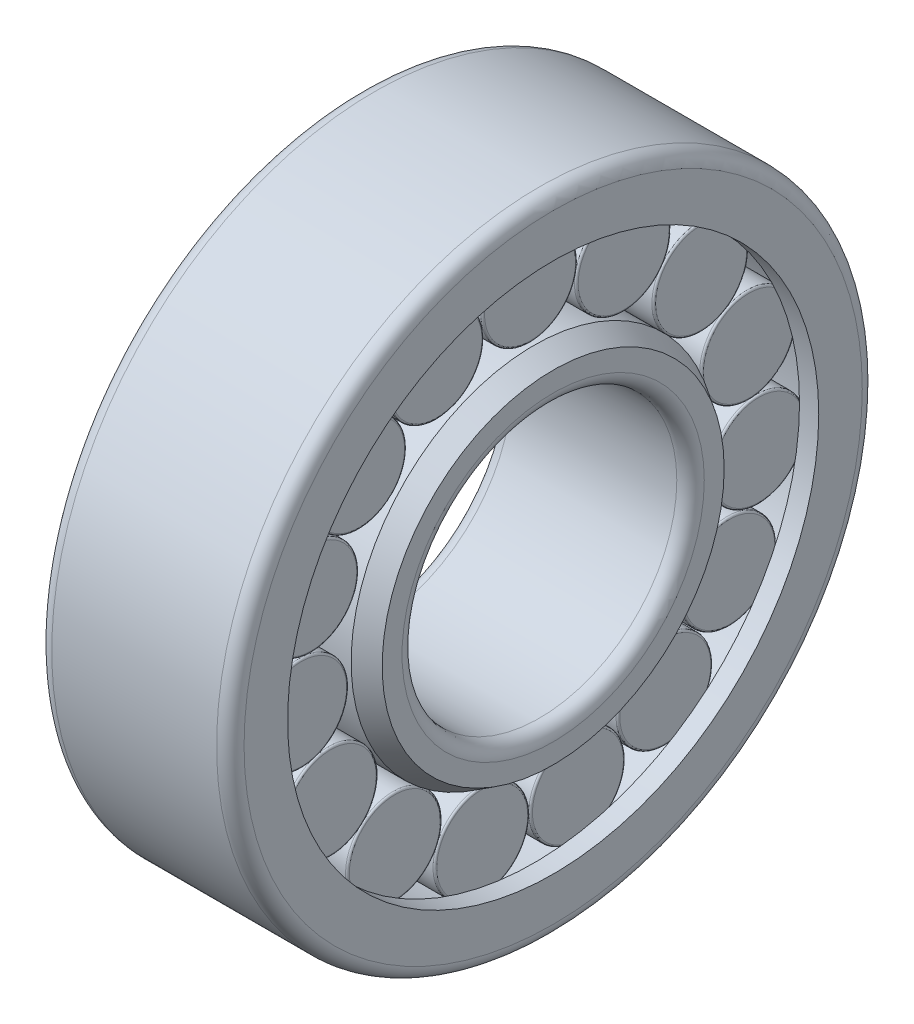
SolidWorks part; units mm, degrees
ref_plane "Plane1" through (0, 0, 0) normal (0, 0, 1) x (1, 0, 0)
ref_plane "Plane2" through (0, 0, 0) normal (0, 1, 0) x (1, 0, 0)
ref_plane "Plane3" through (0, 0, 0) normal (1, 0, 0) x (0, 0, -1)
sketch "Clipboard" plane through (0, 0, 0) normal (0, 0, 1) x (1, 0, 0)
  line L0 (-10, 0) -> (10, 0) construction
  line L1 (0, 0) -> (25.7081, -6.8885)
  line L2 (0, 0) -> (16.7474, -0.2923)
  line L3 (0, 0) -> (40.3788, 0.7048)
  line L4 (0, 0) -> (-22.3573, -0.3902)
  dimension "CLdia" = 16.75
  dimension "Count" = 359
  dimension "Show_count" = 359
  dimension "Max_count" = 15
  dimension "Min_count" = 1
  dimension "Race_OD" = 40.385
  dimension "Race_ID" = 26.615
sketch "OutRacSke" plane through (0, 0, 0) normal (0, 0, 1) x (1, 0, 0)
  line L0 (-5.6, 19.3319) -> (-7, 19.3319)
  line L1 (-7, 19.3319) -> (-7, 22.5)
  line L2 (-6, 23.5) -> (6, 23.5)
  line L3 (7, 22.5) -> (7, 19.3319)
  line L4 (7, 19.3319) -> (5.6, 19.3319)
  line L5 (5.6, 19.3319) -> (5.6, 20.1925)
  line L6 (5.6, 20.1925) -> (-5.6, 20.1925)
  line L7 (-5.6, 20.1925) -> (-5.6, 19.3319)
  line L8 (-90, 0) -> (90, 0) construction
  arc A0 (-7, 22.5) -> (-6, 23.5) centre (-6, 22.5) cw
  arc A1 (6, 23.5) -> (7, 22.5) centre (6, 22.5) cw
  dimension "Race_OD" = 40.385
  dimension "radius" = 1
  dimension "OD" = 47
  dimension "Cyl_Len" = 11.2
  dimension "halfCylLen" = 5.6
  dimension "Width" = 14
  dimension "halfWidth" = 7
  dimension "groove_dp" = 0.8606
revolve "OuterRace" add sketch "OutRacSke" angle 360 about L8
sketch "RolDetSke" plane through (0, 0, 0) normal (0, 0, 1) x (1, 0, 0)
  line L0 (-5.32, 20.0596) -> (-5.32, 16.75)
  line L1 (-5.32, 16.75) -> (5.32, 16.75)
  line L2 (5.32, 16.75) -> (5.32, 20.0596)
  line L3 (5.1821, 20.1975) -> (-5.1821, 20.1975)
  line L4 (-33.6, 16.75) -> (33.6, 16.75) construction
  arc A0 (5.32, 20.0596) -> (5.1821, 20.1975) centre (5.1821, 20.0596) ccw
  arc A1 (-5.1821, 20.1975) -> (-5.32, 20.0596) centre (-5.1821, 20.0596) ccw
  dimension "radius" = 0.1379
  dimension "RolCLRad" = 16.75
  dimension "Length" = 10.64
  dimension "halfLength" = 5.32
  dimension "Roller_diameter" = 6.895
revolve "RollerDetailed" add sketch "RolDetSke" angle 360 about L4
ref_axis "Axis1" through (-50, 0, 0) along (1, 0, 0)
sketch "RolSimSke" plane through (0, 101.6, 0) normal (0, 0, 1) x (1, 0, 0)
  line L0 (-5.32, -81.5404) -> (-5.32, -88.1596)
  line L1 (25.4, -101.6) -> (-25.4, -101.6) construction
  line L2 (5.32, -88.1596) -> (5.32, -81.5404)
  line L3 (5.1821, -81.4025) -> (-5.1821, -81.4025)
  line L5 (5.1821, -88.2975) -> (-5.1821, -88.2975)
  arc A0 (5.32, -81.5404) -> (5.1821, -81.4025) centre (5.1821, -81.5404) ccw
  arc A1 (-5.1821, -81.4025) -> (-5.32, -81.5404) centre (-5.1821, -81.5404) ccw
  arc A2 (5.32, -88.1596) -> (5.1821, -88.2975) centre (5.1821, -88.1596) cw
  arc A3 (-5.1821, -88.2975) -> (-5.32, -88.1596) centre (-5.1821, -88.1596) cw
  dimension "radius" = 0.1379
  dimension "halfLength" = 5.32
  dimension "Roller_diameter" = 6.895
  dimension "D1" = 13.3025
  dimension "Rol_Length" = 10.64
revolve "RollersSimplified" [suppressed] add sketch "RolSimSke" angle 360 about L1
sketch "InsRacSke" plane through (0, 0, 0) normal (0, 0, 1) x (1, 0, 0)
  line L0 (-5.6, 13.3075) -> (-7, 12.4469)
  line L1 (-7, 12.4469) -> (-7, 11)
  line L2 (-6, 10) -> (6, 10)
  line L3 (7, 11) -> (7, 12.4469)
  line L4 (7, 12.4469) -> (5.6, 13.3075)
  line L5 (5.6, 13.3075) -> (-5.6, 13.3075)
  line L6 (-90, 0) -> (90, 0) construction
  line L7 (0, 0) -> (0, 177.8) construction
  arc A0 (-7, 11) -> (-6, 10) centre (-6, 11) ccw
  arc A1 (6, 10) -> (7, 11) centre (6, 11) ccw
  dimension "Race_ID" = 26.615
  dimension "radius" = 1
  dimension "Cyl_Len" = 11.2
  dimension "Width" = 14
  dimension "halfWidth" = 7
  dimension "groove_dp" = 0.8606
  dimension "Bore" = 20
revolve "InnerRace" add sketch "InsRacSke" angle 360 about L6
pattern_circular "RollersDetailed" count 15 every 24 about axis through (-50, 0, 0) along (1, 0, 0) of "RollerDetailed"
sketch "CagSpiSke" plane through (0, 0, 0) normal (0, 0, 1) x (1, 0, 0)
  line L0 (6.3, 15.8881) -> (6.3, 17.6119)
  line L1 (6.3, 17.6119) -> (-6.3, 17.6119)
  line L2 (-6.3, 17.6119) -> (-6.3, 15.8881)
  line L3 (-6.3, 15.8881) -> (6.3, 15.8881)
  line L4 (-90, 0) -> (90, 0) construction
  dimension "Cag_IR" = 31.7762
  dimension "thickness" = 1.7237
  dimension "width" = 12.6
  dimension "halfwidth" = 6.3
revolve "CageSpine" [suppressed] add sketch "CagSpiSke" angle 0.001 about L4
equation "\"CLdia@Clipboard\" =  ( \"Race_OD@Clipboard\" + \"Race_ID@Clipboard\" )  / 4"
equation "\"Race_OD@OutRacSke\" = \"Race_OD@Clipboard\""
equation "\"halfCylLen@OutRacSke\" = \"Cyl_Len@OutRacSke\" / 2"
equation "\"RolCLRad@RolDetSke\" = \"CLdia@Clipboard\""
equation "\"Roller_diameter@RolDetSke\" =  ( \"Race_OD@Clipboard\" - \"Race_ID@Clipboard\" )  / 2 + .01"
equation "\"Roller_diameter@RolSimSke\" =  ( \"Race_OD@Clipboard\" - \"Race_ID@Clipboard\" )  / 2 + .01"
equation "\"radius@RolDetSke\" = \"Roller_diameter@RolDetSke\" / 50"
equation "\"Length@RolDetSke\" = \"Cyl_Len@OutRacSke\" * .95"
equation "\"halfLength@RolDetSke\" = \"Length@RolDetSke\" / 2"
equation "\"thickness@CagSpiSke\"  = \"Roller_diameter@RolDetSke\" * .25"
equation "\"Cag_IR@CagSpiSke\" =  \"RolCLRad@RolDetSke\" * 2 - \"thickness@CagSpiSke\""
equation "\"Rol_Length@RolSimSke\" = \"Cyl_Len@InsRacSke\" * .95"
equation "\"halfLength@RolSimSke\" = \"Rol_Length@RolSimSke\" / 2"
equation "\"radius@RolSimSke\" = \"radius@RolDetSke\""
equation "\"D1@RolSimSke\" = \"CLdia@Clipboard\" -  ( \"Roller_diameter@RolSimSke\" / 2 ) "
equation "\"Max_count@Clipboard\" = int( 3.14159265 / atn(( \"Roller_diameter@RolDetSke\" / 2) / sqr( \"RolCLRad@RolDetSke\"  *  \"RolCLRad@RolDetSke\" - ( \"Roller_diameter@RolDetSke\" / 2) *  ( \"Roller_diameter@RolDetSke\" / 2))))"
equation "\"Max_count@Clipboard\" = ((sgn( \"Max_count@Clipboard\" - \"Count@Clipboard\" )-1)*( \"Max_count@Clipboard\" - \"Count@Clipboard\" ))/-2+ \"Count@Clipboard\""
equation "\"Count@RollersDetailed\" = int( \"Show_count@Clipboard\" ) "
equation "\"Count@RollersDetailed\" = ((sgn( \"Count@RollersDetailed\" - \"Max_count@Clipboard\" )-1)*( \"Count@RollersDetailed\" - \"Max_count@Clipboard\" ))/-2+ \"Max_count@Clipboard\""
equation "\"Count@RollersDetailed\" = ((sgn( \"Count@RollersDetailed\" - \"Min_count@Clipboard\" )+1)*( \"Count@RollersDetailed\" - \"Min_count@Clipboard\"))/2 +\"Min_count@Clipboard\""
equation "\"Angle@RollersDetailed\" = 360.0 / \"Max_count@Clipboard\""
equation "\"radius@InsRacSke\" = \"radius@OutRacSke\""
equation "\"groove_dp@InsRacSke\" = \"groove_dp@OutRacSke\""
equation "\"Width@InsRacSke\" = \"Width@OutRacSke\""
equation "\"halfWidth@OutRacSke\" = \"Width@OutRacSke\" / 2"
equation "\"halfWidth@InsRacSke\" = \"Width@InsRacSke\" / 2"
equation "\"Race_ID@InsRacSke\" = \"Race_ID@Clipboard\""
equation "\"Cyl_Len@InsRacSke\" = \"Cyl_Len@OutRacSke\""
equation "\"Angle@CageSpine\" =  \"Angle@RollersDetailed\" * ( \"Count@RollersDetailed\" -1 + int( \"Count@RollersDetailed\" / \"Max_count@Clipboard\" ) )  + 0.001 -  int( \"Count@RollersDetailed\" / \"Max_count@Clipboard\" ) * 0.001"
equation "\"Angle@CageSpine\" =  \"Angle@CageSpine\" * int( \"Min_count@Clipboard\" / 2) + int(1 / \"Min_count@Clipboard\")  * 0.001"
equation "\"width@CagSpiSke\" =   ( \"Width@InsRacSke\" + \"Cyl_Len@InsRacSke\" )  / 2"
equation "\"halfwidth@CagSpiSke\" = \"width@CagSpiSke\" / 2"
